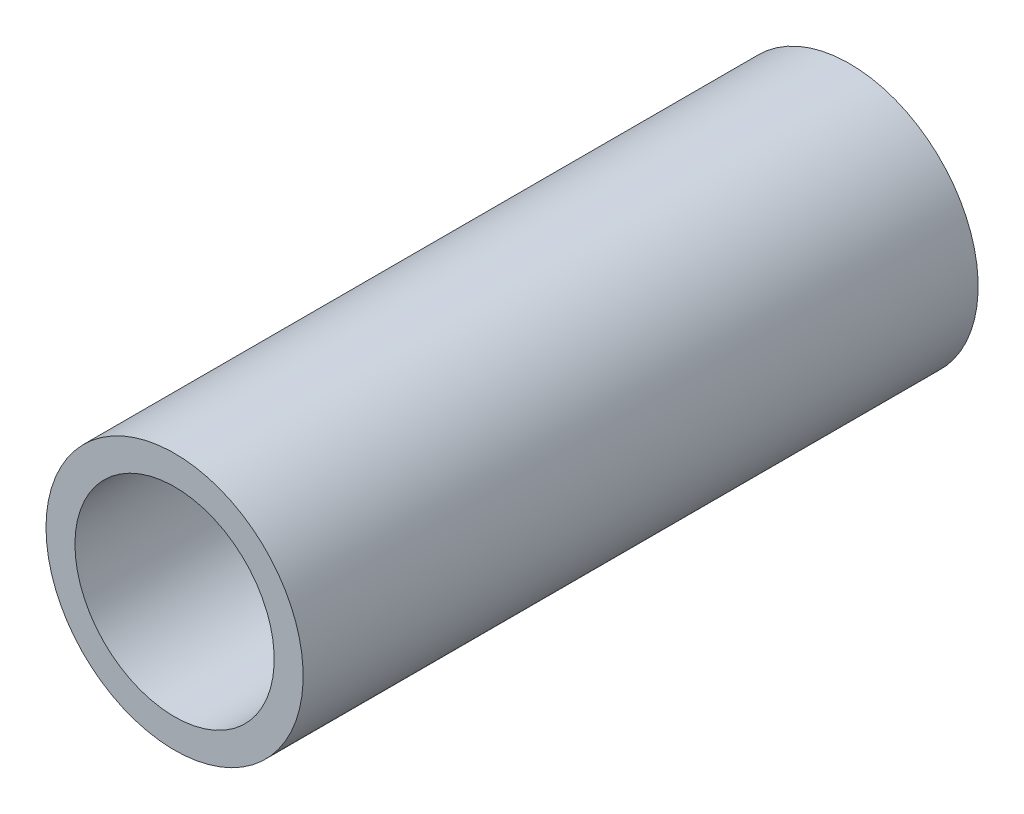
SolidWorks part; units mm, degrees
ref_plane "Front Plane" through (0, 0, 0) normal (0, 0, 1) x (1, 0, 0)
ref_plane "Top Plane" through (0, 0, 0) normal (0, 1, 0) x (1, 0, 0)
ref_plane "Right Plane" through (0, 0, 0) normal (1, 0, 0) x (0, 0, -1)
sketch "Sketch1" plane through (0, 0, 0) normal (0, 0, 1) x (1, 0, 0)
  circle A0 centre (0, 0) radius 3.1
  circle A1 centre (0, 0) radius 4
  dimension "D1" = 6.2
  dimension "D2" = 8
extrude "Boss-Extrude1" add sketch "Sketch1" along normal blind 21
equation "\"iw\"= 6.2mm'o"
equation "\"ow\"= 8mm"
equation "\"h\" = 21mm"
equation "\"D1@Sketch1\"=\"iw\""
equation "\"D2@Sketch1\"=\"ow\""
equation "\"D1@Boss-Extrude1\"=\"h\""
